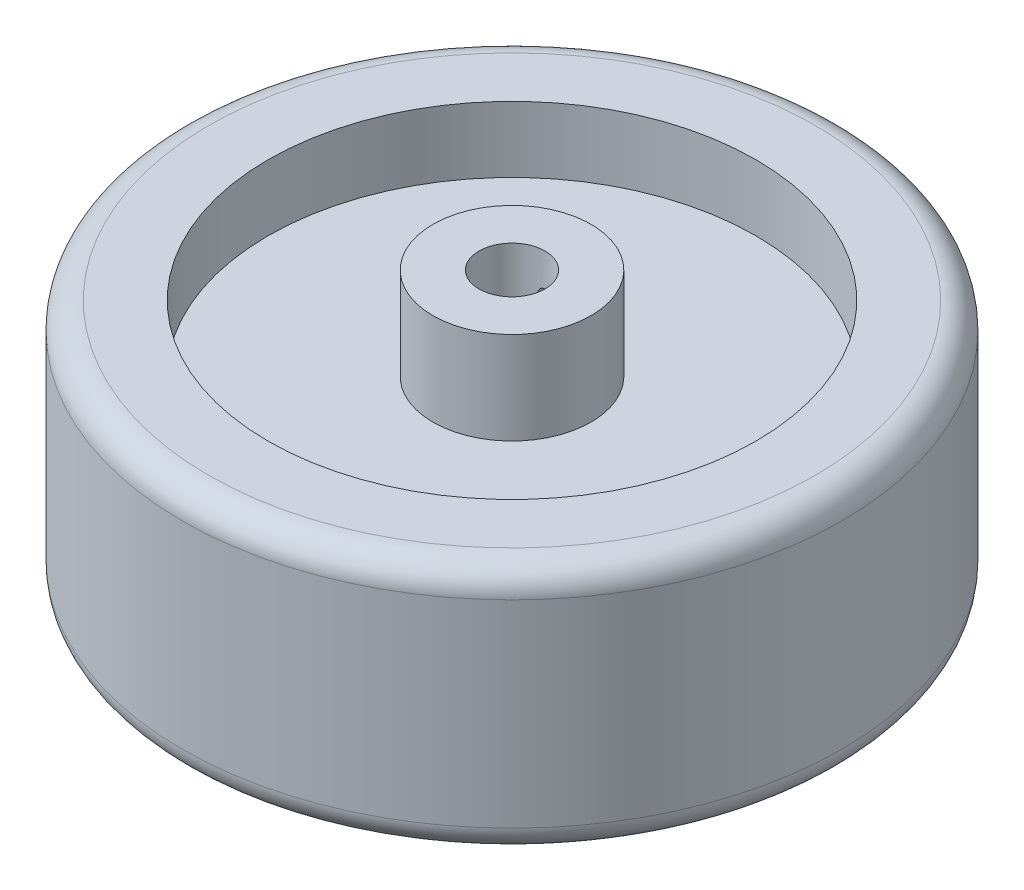
SolidWorks part; units mm, degrees
ref_plane "前视基准面" through (0, 0, 0) normal (0, 0, 1) x (1, 0, 0)
ref_plane "上视基准面" through (0, 0, 0) normal (0, 1, 0) x (1, 0, 0)
ref_plane "右视基准面" through (0, 0, 0) normal (1, 0, 0) x (0, 0, -1)
sketch "Sketch1" plane through (0, 0, 0) normal (0, 1, 0) x (1, 0, 0)
  circle A0 centre (0, 0) radius 50
extrude "Extrude1" add sketch "Sketch1" along normal blind 38
sketch "Sketch2" plane through (0, 0, 0) normal (0, -1, 0) x (1, 0, 0)
  circle A0 centre (0, 0) radius 12
extrude "Extrude2" add sketch "Sketch2" along normal blind 4 and the other way offset from surface (42 mm away) 4 other way up to face at (0, 38, 50)
sketch "Sketch3" plane through (0, -4, 0) normal (0, -1, 0) x (1, 0, 0)
  circle A0 centre (0, 0) radius 5
extrude "Extrude3" cut sketch "Sketch3" against normal blind 77
sketch "Sketch4" plane through (0, 0, 0) normal (0, -1, 0) x (1, 0, 0)
  circle A0 centre (0, 0) radius 37
  circle A1 centre (0, 0) radius 12
  circle A2 centre (0, 0) radius 12
  dimension "D1" = 0
  dimension "D2" = 25
extrude "Extrude4" cut sketch "Sketch4" against normal blind 10
sketch "Sketch5" plane through (0, 38, 0) normal (0, 1, 0) x (1, 0, 0)
  circle A0 centre (0, 0) radius 12 construction
  circle A1 centre (0, 0) radius 37
  circle A2 centre (0, 0) radius 37
  circle A3 centre (0, 0) radius 12
  dimension "D1" = 0
extrude "Extrude6" cut sketch "Sketch5" against normal blind 10
fillet "Fillet1" radius 4 2 edges at (0, 38, 50) (0, 0, 50)
sketch "Sketch6" plane through (0, 0, 0) normal (0, 0, 1) x (1, 0, 0)
  circle A0 centre (0, 36) radius 1
extrude "Extrude7" cut sketch "Sketch6" against normal blind 12
